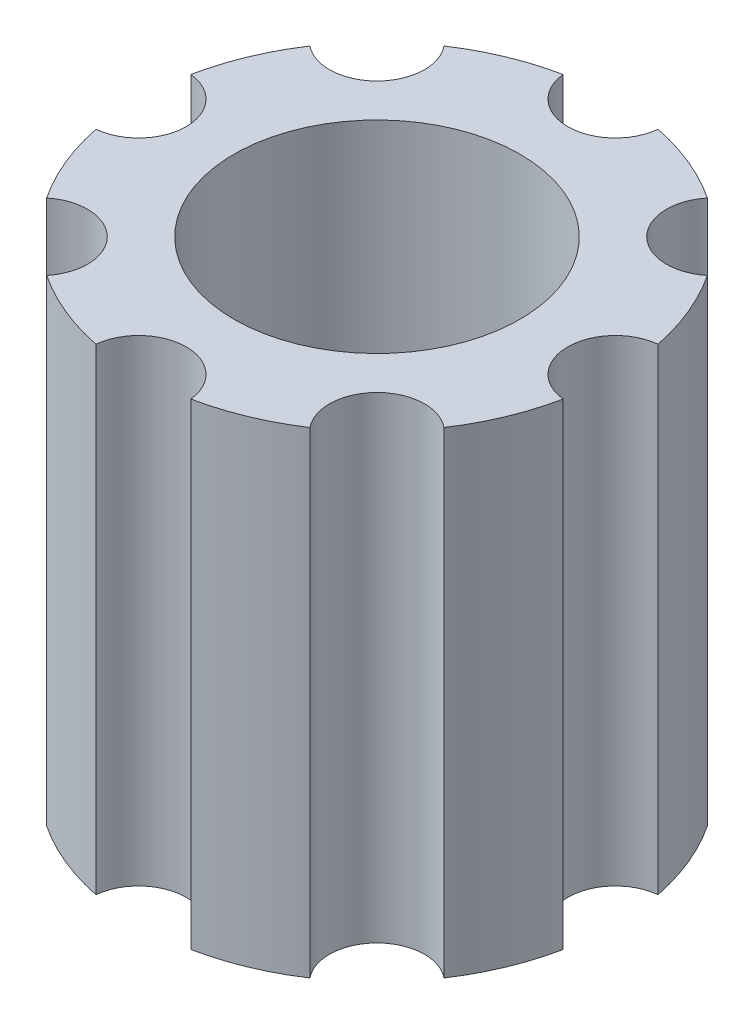
SolidWorks part; units mm, degrees
ref_plane "Front Plane" through (0, 0, 0) normal (0, 0, 1) x (1, 0, 0)
ref_plane "Top Plane" through (0, 0, 0) normal (0, 1, 0) x (1, 0, 0)
ref_plane "Right Plane" through (0, 0, 0) normal (1, 0, 0) x (0, 0, -1)
sketch "Sketch1" plane through (0, 0, 0) normal (0, 1, 0) x (1, 0, 0)
  line L0 (-2.5, 0) -> (2.5, 0) construction
  circle A0 centre (0, 0) radius 2.5
  circle A1 centre (0, 0) radius 1.5
  arc A2 (-2.45, 0.4975) -> (-2.45, -0.4975) centre (-2.5, 0) cw
  arc A3 (-1.3806, 2.0842) -> (-2.0842, 1.3806) centre (-1.7678, 1.7678) cw
  arc A4 (0.4975, 2.45) -> (-0.4975, 2.45) centre (0, 2.5) cw
  arc A5 (2.0842, 1.3806) -> (1.3806, 2.0842) centre (1.7678, 1.7678) cw
  arc A6 (2.45, -0.4975) -> (2.45, 0.4975) centre (2.5, 0) cw
  arc A7 (1.3806, -2.0842) -> (2.0842, -1.3806) centre (1.7678, -1.7678) cw
  arc A8 (-0.4975, -2.45) -> (0.4975, -2.45) centre (0, -2.5) cw
  arc A9 (-2.0842, -1.3806) -> (-1.3806, -2.0842) centre (-1.7678, -1.7678) cw
  point P31 (0, 0)
  dimension "D1" = 5
  dimension "D2" = 3
  dimension "D3" = 0.5
  dimension "D4" = 8
extrude "Boss-Extrude1" add sketch "Sketch1" along normal blind 5 contours L0 A2 A0 A9 A8 A7 A6 A1 | A2 L0 A1 A6 A0 A5 A4 A3
